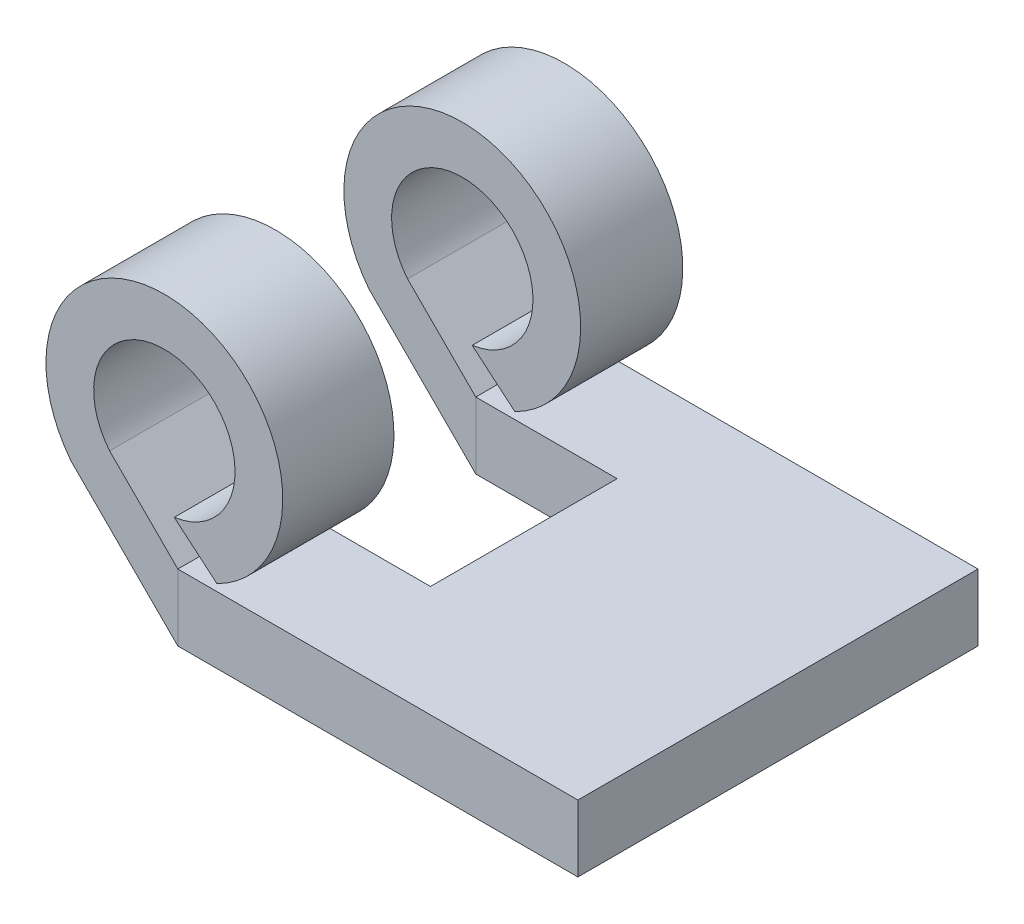
SolidWorks part; units mm, degrees
material "1060 Alloy"
ref_plane "Front Plane" through (0, 0, 0) normal (0, 0, 1) x (1, 0, 0)
ref_plane "Top Plane" through (0, 0, 0) normal (0, 1, 0) x (1, 0, 0)
ref_plane "Right Plane" through (0, 0, 0) normal (1, 0, 0) x (0, 0, -1)
sketch "Sketch1" plane through (0, 0, 0) normal (0, 0, 1) x (1, 0, 0)
  line L1 (0, 0) -> (19.05, 0)
  line L2 (0, 0) -> (0, 3.175)
  line L3 (0, 3.175) -> (19.05, 3.175)
  line L4 (19.05, 0) -> (19.05, 3.175)
  dimension "D1" = 3.175
  dimension "D2" = 19.05
extrude "Boss-Extrude1" add sketch "Sketch1" along normal blind 19.05
sketch "Sketch2" plane through (0, 0, 19.05) normal (0, 0, 1) x (1, 0, 0)
  line L0 (0, 3.175) -> (-3.2465, 6.4215)
  line L1 (0, 0) -> (-5.0857, 5.0857)
  line L2 (-0.1694, 5.2208) -> (1.8619, 3.5033)
  line L3 (0, 0) -> (0, 3.175)
  arc A0 (-3.2465, 6.4215) -> (-0.1694, 5.2208) centre (-0.6419, 8.5529) cw
  arc A1 (-5.0857, 5.0857) -> (1.8619, 3.5033) centre (-0.6419, 8.5529) cw
  dimension "D1" = 6.731
extrude "Boss-Extrude2" add sketch "Sketch2" against normal blind 19.05 separate body
sketch "Sketch3" plane through (0, 0, 0) normal (0, -1, 0) x (1, 0, 0)
  line L0 (-5.0857, 19.05) -> (0, 19.05) construction
  line L1 (6.7333, 13.7541) -> (-7.7658, 13.7541)
  line L2 (6.7333, 13.7541) -> (6.7333, 4.8641)
  line L3 (6.7333, 4.8641) -> (-7.7658, 4.8641)
  line L4 (-7.7658, 13.7541) -> (-7.7658, 4.8641)
  dimension "D1" = 5.2959
  dimension "D2" = 8.89
extrude "Cut-Extrude1" cut sketch "Sketch3" against normal blind 19.05
